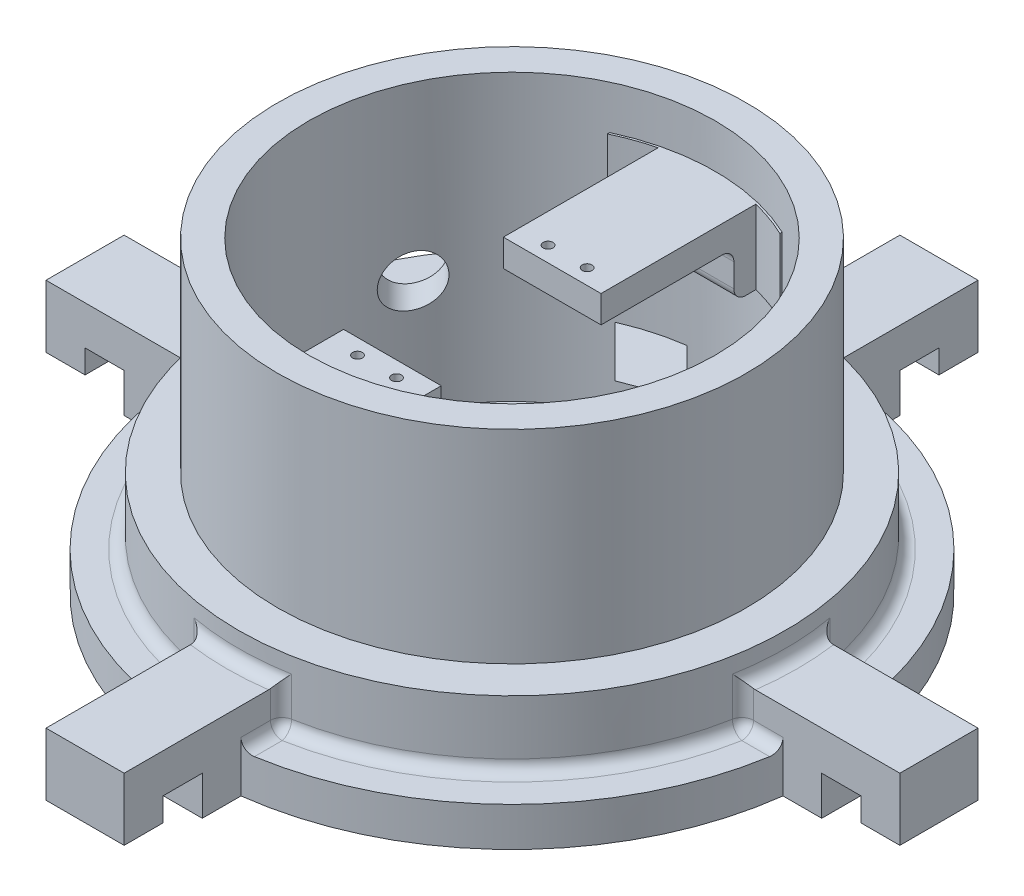
SolidWorks part; units mm, degrees
material "ABS"
ref_plane "Front Plane" through (0, 0, 0) normal (0, 0, 1) x (1, 0, 0)
ref_plane "Top Plane" through (0, 0, 0) normal (0, 1, 0) x (1, 0, 0)
ref_plane "Right Plane" through (0, 0, 0) normal (1, 0, 0) x (0, 0, -1)
sketch "Sketch1" plane through (0, 0, 0) normal (0, 1, 0) x (1, 0, 0)
  circle A0 centre (0, 0) radius 70
  dimension "D1" = 140
extrude "Boss-Extrude1" add sketch "Sketch1" along normal blind 80
sketch "Sketch2" plane through (0, 80, 0) normal (0, 1, 0) x (1, 0, 0)
  circle A0 centre (0, 0) radius 60
  dimension "D1" = 120
extrude "Cut-Extrude1" cut sketch "Sketch2" against normal blind 90
sketch "Sketch3" plane through (0, 0, 0) normal (0, -1, 0) x (1, 0, 0)
  line L0 (0, 90.5056) -> (0, -100.2243) construction
  line L1 (-113.5876, 0) -> (122.6989, 0) construction
  line L2 (94.282, 10) -> (94.282, -10)
  line L3 (94.282, -10) -> (69.282, -10)
  line L4 (94.282, 10) -> (69.282, 10)
  line L5 (10, -94.282) -> (10, -69.282)
  line L6 (-10, -94.282) -> (-10, -69.282)
  line L7 (10, -94.282) -> (-10, -94.282)
  line L8 (-94.282, -10) -> (-69.282, -10)
  line L9 (-94.282, 10) -> (-69.282, 10)
  line L10 (-94.282, -10) -> (-94.282, 10)
  line L11 (-10, 94.282) -> (-10, 69.282)
  line L12 (10, 94.282) -> (10, 69.282)
  line L13 (-10, 94.282) -> (10, 94.282)
  arc A0 (69.282, -10) -> (69.282, 10) centre (0, 0) ccw
  arc A1 (-10, -69.282) -> (10, -69.282) centre (0, 0) ccw
  arc A3 (-69.282, 10) -> (-69.282, -10) centre (0, 0) ccw
  arc A4 (10, 69.282) -> (-10, 69.282) centre (0, 0) ccw
  point P25 (0, 0)
  dimension "D2" = 20
  dimension "D3" = 10
  dimension "D4" = 25
  dimension "D1" = 4
extrude "Boss-Extrude2" add sketch "Sketch3" against normal blind 20
sketch "Sketch5" plane through (0, 0, 0) normal (0, -1, 0) x (1, 0, 0)
  circle A0 centre (0, 0) radius 70
extrude "Boss-Extrude3" add sketch "Sketch5" against normal blind 10
sketch "Sketch6" plane through (0, 0, 0) normal (0, -1, 0) x (1, 0, 0)
  circle A0 centre (0, 0) radius 80
  dimension "D1" = 160
extrude "Boss-Extrude5" add sketch "Sketch6" against normal blind 10
sketch "Sketch7" plane through (0, 0, 94.282) normal (0, 0, 1) x (1, 0, 0)
  line L1 (-10, 20) -> (10, 20)
  line L2 (-10, 20) -> (-10, 0)
  line L3 (-10, 0) -> (10, 0)
  line L4 (10, 20) -> (10, 0)
  line L5 (-10, 20) -> (10, 0) construction
  line L6 (-10, 0) -> (10, 20) construction
  point P0 (0, 10)
extrude "Boss-Extrude6" add sketch "Sketch7" along normal blind 15
pattern_circular "CirPattern1" count 4 over 360 about axis through (0, 0, 0) along (0, 1, 0) of "Boss-Extrude6"
fillet "Fillet3" radius 3 12 edges at (-10, 15, -69.282) (-10, 15, 69.282) (0, 20, -70) (0, 20, 70) (10, 15, -69.282) (10, 15, 69.282) (-69.282, 15, -10) (69.282, 15, -10) (-70, 20, 0) (70, 20, 0) (-69.282, 15, 10) (69.282, 15, 10)
fillet "Fillet4" radius 3 20 edges at (-10, 10, 75.6028) (-10.6975, 10, 69.91) (-75.6028, 10, 10) (-69.91, 10, 10.6975) (-75.6028, 10, -10) (-69.91, 10, -10.6975) (-10, 10, -75.6028) (-10.6975, 10, -69.91) (10, 10, -75.6028) (10.6975, 10, -69.91) (75.6028, 10, -10) (69.91, 10, -10.6975) (75.6028, 10, 10) (69.91, 10, 10.6975) (10, 10, 75.6028) (10.6975, 10, 69.91) (-49.4975, 10, 49.4975) (-49.4975, 10, -49.4975) (49.4975, 10, -49.4975) (49.4975, 10, 49.4975)
sketch "Sketch11" plane through (0, 0, 0) normal (0, -1, 0) x (1, 0, 0)
  line L0 (-10, -79.3725) -> (-10, -109.282) construction
  line L1 (-10, -99.282) -> (10, -99.282)
  line L2 (-10, -99.282) -> (-10, -89.282)
  line L3 (-10, -89.282) -> (10, -89.282)
  line L4 (10, -99.282) -> (10, -89.282)
  line L5 (10, -109.282) -> (10, -79.3725) construction
  dimension "D1" = 10
  dimension "D2" = 10
extrude "Cut-Extrude3" cut sketch "Sketch11" against normal blind 10
pattern_circular "CirPattern5" count 4 every 90 about axis through (0, 0, 0) along (0, 1, 0) of "Cut-Extrude3"
sketch "Sketch13" plane through (0, 10, 0) normal (0, 1, 0) x (1, 0, 0)
  circle A1 centre (0, 0) radius 60
  circle A2 centre (0, 0) radius 60
  dimension "D1" = 0
extrude "Cut-Extrude4" cut sketch "Sketch13" against normal blind 10
sketch "Sketch15" plane through (0, 0, 0) normal (0, -1, 0) x (1, 0, 0)
  circle A0 centre (0, 0) radius 60
extrude "Boss-Extrude7" add sketch "Sketch15" against normal blind 6
sketch "Sketch16" plane through (0, 0, 0) normal (0, -1, 0) x (1, 0, 0)
  circle A0 centre (0, 0) radius 47.5
  dimension "D1" = 95
extrude "Cut-Extrude5" cut sketch "Sketch16" against normal blind 3
sketch "Sketch17" plane through (0, 3, 0) normal (0, -1, 0) x (1, 0, 0)
  circle A0 centre (0, 0) radius 46.5
  dimension "D1" = 93
extrude "Cut-Extrude6" cut sketch "Sketch17" against normal blind 13
sketch "Sketch18" plane through (0, 6, 0) normal (0, 1, 0) x (1, 0, 0)
  circle A0 centre (0, 0) radius 46.5
  circle A1 centre (0, 0) radius 60
extrude "Boss-Extrude8" add sketch "Sketch18" along normal blind 73
sketch "Sketch19" plane through (0, 80, 0) normal (0, 1, 0) x (1, 0, 0)
  circle A0 centre (0, 0) radius 60
  circle A1 centre (0, 0) radius 70
extrude "Cut-Extrude7" cut sketch "Sketch19" against normal blind 53
sketch "Sketch20" plane through (0, 79, 0) normal (0, 1, 0) x (1, 0, 0)
  circle A0 centre (0, 0) radius 46.5
  circle A1 centre (0, 0) radius 52
  dimension "D1" = 104
extrude "Cut-Extrude8" cut sketch "Sketch20" against normal blind 53
sketch "Sketch21" plane through (0, 26, 0) normal (0, 1, 0) x (1, 0, 0)
  circle A0 centre (0, 0) radius 46.5
  circle A1 centre (0, 0) radius 52
extrude "Cut-Extrude9" cut sketch "Sketch21" against normal blind 13
sketch "Sketch22" plane through (0, 13, 0) normal (0, 1, 0) x (1, 0, 0)
  circle A0 centre (0, 0) radius 46.5
  circle A1 centre (0, 0) radius 52
extrude "Cut-Extrude10" cut sketch "Sketch22" against normal blind 7
ref_plane "Plane2" through (-44.6863, 0, -44.6863) normal (-0.7071, 0, -0.7071) x (-0.7071, 0, 0.7071)
sketch "Sketch24" plane through (-44.6863, 0, -44.6863) normal (-0.7071, 0, -0.7071) x (-0.7071, 0, 0.7071)
  line L0 (-39.8917, 13) -> (39.8917, 13) construction
  line L1 (-31.6489, 13) -> (-18.6489, 13)
  line L2 (-31.6489, 13) -> (-31.6489, 26)
  line L3 (-31.6489, 26) -> (-18.6489, 26)
  line L4 (-18.6489, 13) -> (-18.6489, 26)
  dimension "D1" = 13
  dimension "D2" = 13
extrude "Cut-Extrude14" cut sketch "Sketch24" against normal mid plane 77
sketch "Sketch26" plane through (0, 0, 0) normal (0, 0, 1) x (1, 0, 0)
  line L0 (52, 79) -> (-52, 79) construction
  line L1 (-22.0792, 48.8395) -> (22.0792, 48.8395)
  line L2 (-22.0792, 48.8395) -> (-22.0792, 79)
  line L3 (-22.0792, 79) -> (22.0792, 79)
  line L4 (22.0792, 48.8395) -> (22.0792, 79)
  line L5 (-22.0792, 48.8395) -> (22.0792, 79) construction
  line L6 (-22.0792, 79) -> (22.0792, 48.8395) construction
  point P0 (0, 63.9198)
extrude "Boss-Extrude9" add sketch "Sketch26" against normal up to surface (47.0798 mm away)
sketch "Sketch27" plane through (0, 0, 0) normal (0, 0, 1) x (1, 0, 0)
  line L1 (-22.0792, 79) -> (22.0792, 79)
  line L2 (-22.0792, 79) -> (-22.0792, 48.8395)
  line L3 (-22.0792, 48.8395) -> (22.0792, 48.8395)
  line L4 (22.0792, 79) -> (22.0792, 48.8395)
extrude "Boss-Extrude10" add sketch "Sketch27" along normal up to surface (47.0798 mm away)
sketch "Sketch28" plane through (0, 79, 0) normal (0, 1, 0) x (1, 0, 0)
  circle A0 centre (0, 0) radius 52
extrude "Cut-Extrude15" cut sketch "Sketch28" against normal blind 11.2
sketch "Sketch29" plane through (0, 67.8, 0) normal (0, 1, 0) x (1, 0, 0)
  line L0 (-10, 10.18) -> (10, 10.18)
  line L1 (-10, 17.13) -> (10, 17.13)
  line L2 (-10, 17.13) -> (-10, -37.45)
  line L3 (-10, -37.45) -> (10, -37.45)
  line L4 (10, 17.13) -> (10, -37.45)
  line L5 (-10, -30.5) -> (10, -30.5)
  circle A3 centre (-5, 14.23) radius 1.25
  circle A4 centre (5, 14.23) radius 1.25
  circle A5 centre (-5, -34.55) radius 1.25
  circle A6 centre (5, -34.55) radius 1.25
  point P0 (0, 0)
  point P10 (5, 14.23)
  point P11 (-5, 14.23)
  point P12 (5, -34.55)
  point P13 (-5, -34.55)
  dimension "D13" = 2.5
  dimension "D1" = 54.58
  dimension "D2" = 20
  dimension "D3" = 17.13
  dimension "D4" = 10
  dimension "D5" = 6.95
  dimension "D6" = 6.95
  dimension "D7" = 10
  dimension "D8" = 10
  dimension "D9" = 5
  dimension "D10" = 5
  dimension "D11" = 2.9
  dimension "D12" = 2.9
extrude "Cut-Extrude16" cut sketch "Sketch29" against normal through all contours A3 | A4 | A6 | A5
sketch "Sketch30" plane through (0, 67.8, 0) normal (0, 1, 0) x (1, 0, 0)
  line L0 (-22.0792, -47.0798) -> (-22.0792, 47.0798) construction
  line L1 (-22.0792, 10.29) -> (22.0792, 10.29)
  line L2 (-22.0792, 10.29) -> (-22.0792, -30.61)
  line L3 (-22.0792, -30.61) -> (22.0792, -30.61)
  line L4 (22.0792, 10.29) -> (22.0792, -30.61)
  line L5 (22.0792, 47.0798) -> (22.0792, -47.0798) construction
  circle A0 centre (-5, 14.23) radius 1.25 construction
  dimension "D2" = 3.94
  dimension "D1" = 40.9
extrude "Cut-Extrude17" cut sketch "Sketch30" against normal through all
sketch "Sketch32" plane through (0, 67.8, 0) normal (0, 1, 0) x (1, 0, 0)
  line L0 (12.5, 49.9254) -> (12.5, -49.9254)
  line L1 (-12.5, 49.9254) -> (-12.5, -49.9254)
  arc A0 (-12.5, 49.9254) -> (-12.5, -49.9254) centre (0, 0) ccw
  arc A1 (12.5, -49.9254) -> (12.5, 49.9254) centre (0, 0) ccw
  dimension "D1" = 25
  dimension "D2" = 12.5
extrude "Cut-Extrude18" cut sketch "Sketch32" against normal blind 41.2
sketch "Sketch34" plane through (0, 0, -10.29) normal (0, 0, 1) x (1, 0, 0)
  line L0 (-12.5, 67.8) -> (-12.5, 48.8395) construction
  line L1 (12.5, 48.8395) -> (-12.5, 48.8395)
  line L2 (12.5, 48.8395) -> (12.5, 60.8395)
  line L3 (12.5, 60.8395) -> (-12.5, 60.8395)
  line L4 (-12.5, 48.8395) -> (-12.5, 60.8395)
  dimension "D1" = 12
extrude "Cut-Extrude19" cut sketch "Sketch34" against normal blind 34 and the other way blind 56
fillet "Fillet5" radius 3 4 edges at (0, 48.8395, -44.29) (0, 60.8395, -44.29) (0, 60.8395, 45.71) (0, 48.8395, 45.71)
sketch "Sketch36" plane through (0, 6, 0) normal (0, 1, 0) x (1, 0, 0)
  line L3 (41.1266, 23.7837) -> (44.8257, 26.3563)
  line L4 (35.9209, 29.7983) -> (40.3128, 32.8463)
  line L7 (29.222, 25.1492) -> (33.7418, 18.6489)
  line L8 (29.222, 25.1492) -> (35.9209, 29.7983)
  line L9 (33.7418, 18.6489) -> (41.1266, 23.7837)
  circle A0 centre (0, 0) radius 46.5 construction
  arc A3 (-35.7844, -29.6939) -> (-35.7817, -29.6971) centre (0, 0) ccw
  arc A7 (35.9209, 29.7983) -> (35.7817, 29.6971) centre (38.2015, 26.5121) ccw
  arc A8 (40.3387, 23.1309) -> (40.2956, 23.2059) centre (0, 0) ccw
  arc A10 (35.7817, 29.6971) -> (35.7793, 29.7) centre (0, 0) ccw
  arc A11 (44.8257, 26.3563) -> (40.3128, 32.8463) centre (0, 0) ccw
  dimension "D5" = 13.5
extrude "Boss-Extrude11" add sketch "Sketch36" along normal blind 7 contours L8 L7 L9 L3 A11 L4
pattern_circular "CirPattern6" count 2 every 180 about axis through (0, 0, 0) along (0, 1, 0) of "Boss-Extrude11"
sketch "Sketch37" plane through (0, 0, 0) normal (0, -1, 0) x (1, 0, 0)
  line L1 (-109.282, 10) -> (-99.282, 10)
  line L2 (-109.282, 10) -> (-109.282, -10)
  line L3 (-109.282, -10) -> (-99.282, -10)
  line L4 (-99.282, 10) -> (-99.282, -10)
extrude "Cut-Extrude20" cut sketch "Sketch37" against normal blind 4
pattern_circular "CirPattern7" count 4 over 360 about axis through (0, 26, 0) along (0, 1, 0) of "Cut-Extrude20"
sketch "Sketch38" plane through (-44.6863, 0, -44.6863) normal (-0.7071, 0, -0.7071) x (-0.7071, 0, 0.7071)
  circle A0 centre (17.896, 35.015) radius 6.5
  point P2 (17.896, 35.015)
  dimension "D1" = 13
extrude "Cut-Extrude21" cut sketch "Sketch38" against normal blind 30
